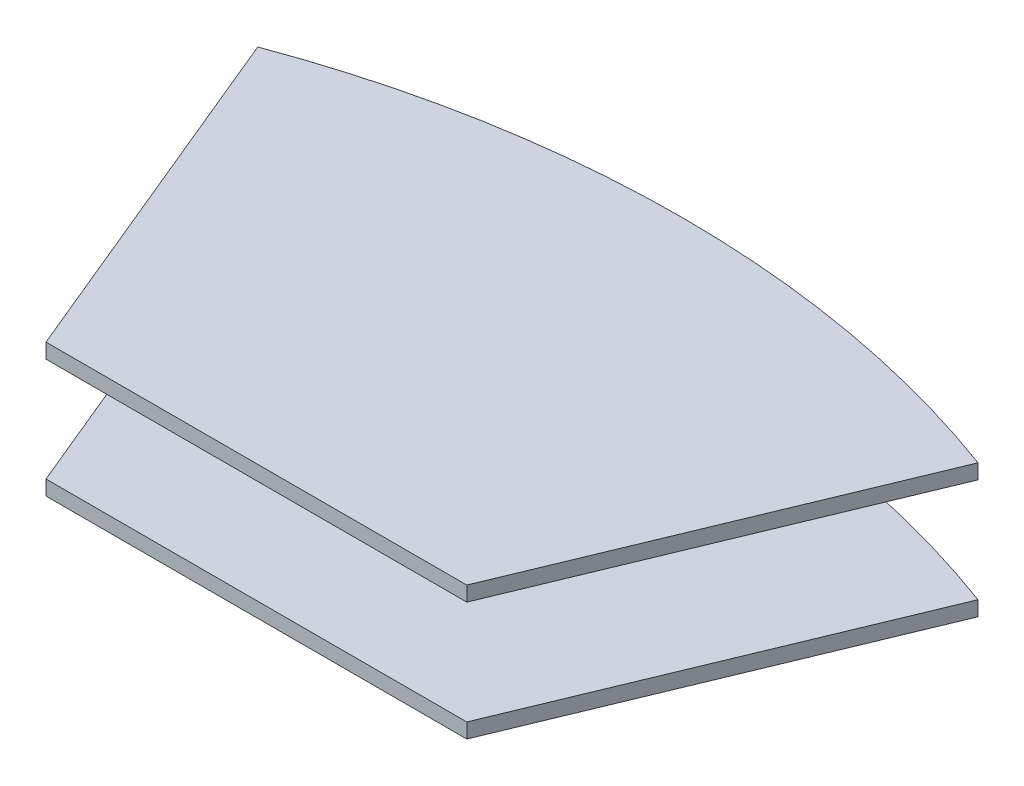
SolidWorks part; units mm, degrees
ref_plane "Front Plane" through (0, 0, 0) normal (0, 0, 1) x (1, 0, 0)
ref_plane "Top Plane" through (0, 0, 0) normal (0, 1, 0) x (1, 0, 0)
ref_plane "Right Plane" through (0, 0, 0) normal (1, 0, 0) x (0, 0, -1)
sketch "Sketch1" plane through (0, 0, 0) normal (0, 1, 0) x (1, 0, 0)
  line L0 (0, 112.1679) -> (0, -167.6521) construction
  line L1 (-121.5, 46.9521) -> (-70.9858, -75)
  line L2 (-70.9858, -75) -> (70.9858, -75)
  line L3 (121.5, 46.9521) -> (70.9858, -75)
  arc A0 (-121.5, 46.9521) -> (121.5, 46.9521) centre (0, -281.2822) cw
  point P9 (0, -75)
  dimension "D1" = 350
  dimension "D2" = 132
  dimension "D3" = 243
  dimension "D4" = 22.5
  dimension "D5" = 75
extrude "Boss-Extrude1" add sketch "Sketch1" along normal blind 5
sketch "Sketch2" plane through (0, 5, 0) normal (0, 1, 0) x (1, 0, 0)
  line L0 (-48.8332, 2.1753) -> (-40.1339, -18.8268)
  line L1 (-30.8951, -25) -> (30.8951, -25)
  line L2 (40.1339, -18.8268) -> (48.8332, 2.1753)
  line L3 (-121.5, 46.9521) -> (-70.9858, -75)
  line L4 (-70.9858, -75) -> (70.9858, -75)
  line L5 (70.9858, -75) -> (121.5, 46.9521)
  line L6 (-121.5, 46.9521) -> (-70.9858, -75) construction
  line L7 (-70.9858, -75) -> (70.9858, -75) construction
  line L8 (70.9858, -75) -> (121.5, 46.9521) construction
  line L9 (37.5769, -25) -> (53.6799, 13.8762) construction
  line L10 (-37.5769, -25) -> (37.5769, -25) construction
  line L11 (-53.6799, 13.8762) -> (-37.5769, -25) construction
  arc A0 (40.9598, 15.9085) -> (-40.9598, 15.9085) centre (0, -281.2822) ccw
  arc A1 (121.5, 46.9521) -> (-121.5, 46.9521) centre (0, -281.2822) ccw
  arc A2 (121.5, 46.9521) -> (-121.5, 46.9521) centre (0, -281.2822) ccw construction
  arc A3 (53.6799, 13.8762) -> (-53.6799, 13.8762) centre (0, -281.2822) ccw construction
  arc A4 (40.9598, 15.9085) -> (48.8332, 2.1753) centre (39.5944, 6.0021) cw
  arc A5 (40.1339, -18.8268) -> (30.8951, -25) centre (30.8951, -15) cw
  arc A6 (-40.1339, -18.8268) -> (-30.8951, -25) centre (-30.8951, -15) ccw
  arc A7 (-48.8332, 2.1753) -> (-40.9598, 15.9085) centre (-39.5944, 6.0021) cw
  dimension "D3" = 10
  dimension "D1" = 0
  dimension "D2" = 50
extrude "Boss-Extrude2" add sketch "Sketch2" along normal blind 35
sketch "Sketch3" plane through (0, 40, 0) normal (0, 1, 0) x (1, 0, 0)
  line L3 (-121.5, 46.9521) -> (-70.9858, -75)
  line L4 (-70.9858, -75) -> (70.9858, -75)
  line L5 (70.9858, -75) -> (121.5, 46.9521)
  line L6 (-121.5, 46.9521) -> (-70.9858, -75)
  line L7 (-70.9858, -75) -> (70.9858, -75)
  line L8 (70.9858, -75) -> (121.5, 46.9521)
  arc A1 (121.5, 46.9521) -> (-121.5, 46.9521) centre (0, -281.2822) ccw
  arc A2 (121.5, 46.9521) -> (-121.5, 46.9521) centre (0, -281.2822) ccw
  dimension "D1" = 0
extrude "Boss-Extrude3" add sketch "Sketch3" along normal blind 5
